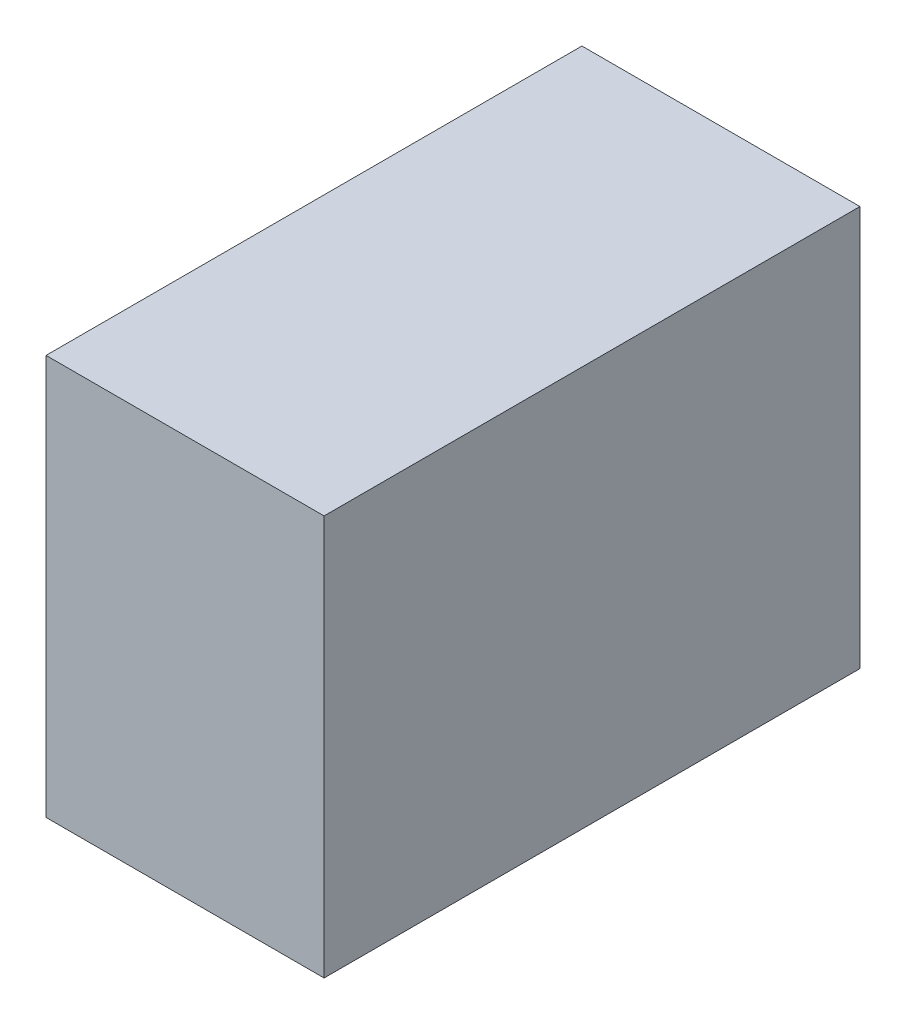
SolidWorks part; units mm, degrees
ref_plane "Front Plane" through (0, 0, 0) normal (0, 0, 1) x (1, 0, 0)
ref_plane "Top Plane" through (0, 0, 0) normal (0, 1, 0) x (1, 0, 0)
ref_plane "Right Plane" through (0, 0, 0) normal (1, 0, 0) x (0, 0, -1)
sketch "Sketch1" plane through (0, 0, 0) normal (1, 0, 0) x (0, 0, -1)
  line L1 (0, 0) -> (97.9052, 0)
  line L2 (0, 0) -> (0, 73.115)
  line L3 (0, 73.115) -> (97.9052, 73.115)
  line L4 (97.9052, 0) -> (97.9052, 73.115)
extrude "Extrude1" add sketch "Sketch1" against normal blind 50.8
